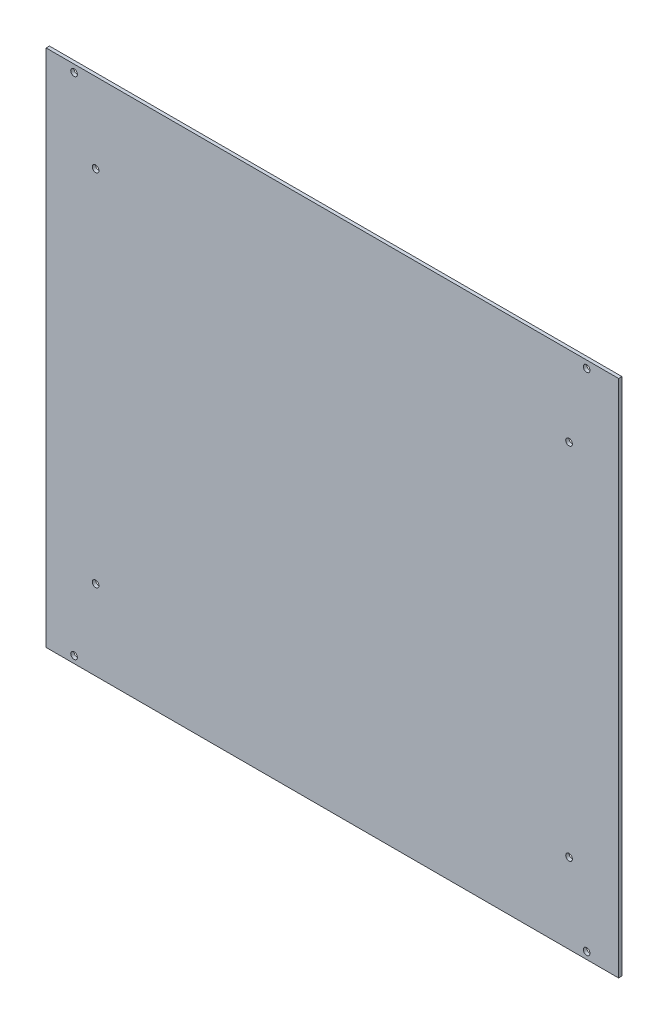
SolidWorks part; units mm, degrees
ref_plane "Front Plane" through (0, 0, 0) normal (0, 0, 1) x (1, 0, 0)
ref_plane "Top Plane" through (0, 0, 0) normal (0, 1, 0) x (1, 0, 0)
ref_plane "Right Plane" through (0, 0, 0) normal (1, 0, 0) x (0, 0, -1)
sketch "Sketch1" plane through (0, 0, 0) normal (0, 0, 1) x (1, 0, 0)
  line L1 (-273.05, -247.65) -> (273.05, -247.65)
  line L2 (-273.05, -247.65) -> (-273.05, 247.65)
  line L3 (-273.05, 247.65) -> (273.05, 247.65)
  line L4 (273.05, -247.65) -> (273.05, 247.65)
  line L5 (-273.05, -247.65) -> (273.05, 247.65) construction
  line L6 (-273.05, 247.65) -> (273.05, -247.65) construction
  point P0 (0, 0)
  dimension "D1" = 546.1
  dimension "D2" = 495.3
extrude "Boss-Extrude1" add sketch "Sketch1" along normal blind 3.175 contours L2 L1 L4 L3
sketch "Sketch3" plane through (0, 0, 3.175) normal (0, 0, 1) x (1, 0, 0)
  line L0 (0, 0) -> (0, 77.5284)
  line L3 (0, 0) -> (-70.16, 0)
  circle A0 centre (-225.806, 171.45) radius 3.175
  circle A1 centre (225.806, 171.45) radius 3.175
  circle A2 centre (225.806, -171.45) radius 3.175
  circle A3 centre (-225.806, -171.45) radius 3.175
  point P12 (0, 0)
extrude "Cut-Extrude2" cut sketch "Sketch3" against normal blind 3.175 contours A0 | A1 | A3 | A2
sketch "Sketch4" plane through (0, 0, 3.175) normal (0, 0, 1) x (1, 0, 0)
  circle A0 centre (-246.3672, 240.6518) radius 3.175
  circle A1 centre (-246.3672, -240.983) radius 3.175
  circle A2 centre (242.5828, -240.983) radius 3.175
  circle A3 centre (242.5828, 240.6518) radius 3.175
extrude "Cut-Extrude3" cut sketch "Sketch4" against normal blind 16.764 contours A0 | A3 | A2 | A1
